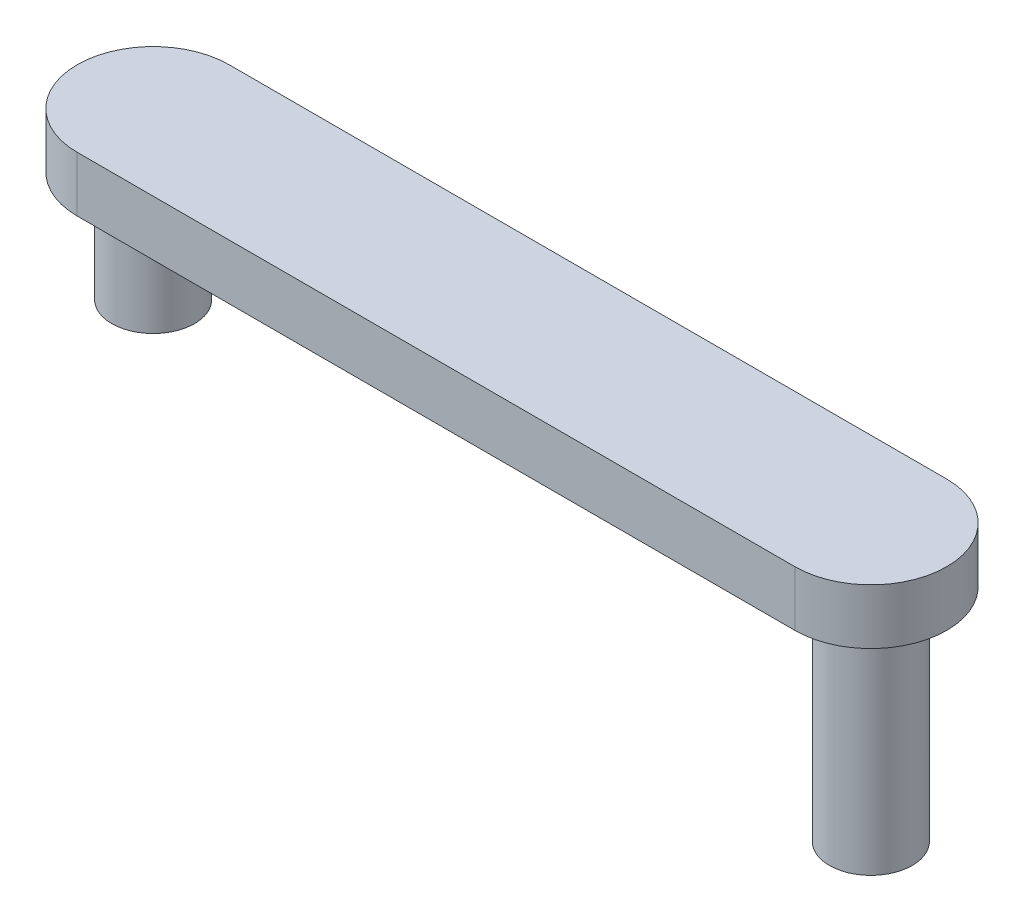
SolidWorks part; units mm, degrees
ref_plane "Front Plane" through (0, 0, 0) normal (0, 0, 1) x (1, 0, 0)
ref_plane "Top Plane" through (0, 0, 0) normal (0, 1, 0) x (1, 0, 0)
ref_plane "Right Plane" through (0, 0, 0) normal (1, 0, 0) x (0, 0, -1)
sketch "Sketch1" plane through (0, 0, 0) normal (0, 1, 0) x (1, 0, 0)
  line L0 (-11.8981, 0) -> (13.5671, 0) construction
  circle A0 centre (0, 0) radius 1.5
  dimension "D1" = 3
extrude "Boss-Extrude1" add sketch "Sketch1" along normal blind 4
sketch "Sketch2" plane through (0, 4, 0) normal (0, 1, 0) x (1, 0, 0)
  line L0 (-6.8584, 0) -> (34.6919, 0) construction
  line L1 (0, 2.75) -> (26, 2.75)
  line L2 (0, -2.75) -> (26, -2.75)
  arc A0 (0, 2.75) -> (0, -2.75) centre (0, 0) ccw
  arc A1 (26, -2.75) -> (26, 2.75) centre (26, 0) ccw
  dimension "D1" = 5.5
  dimension "D2" = 5.5
  dimension "D3" = 26
extrude "Boss-Extrude2" add sketch "Sketch2" along normal blind 2
sketch "Sketch3" plane through (0, 4, 0) normal (0, -1, 0) x (1, 0, 0)
  arc A0 (26, -2.75) -> (26, 2.75) centre (26, 0) ccw construction
  arc A1 (26, -2.75) -> (26, 2.75) centre (26, 0) ccw
  circle A2 centre (26, 0) radius 1.5
  dimension "D1" = 3
extrude "Boss-Extrude3" add sketch "Sketch3" along normal blind 8 contours A2
